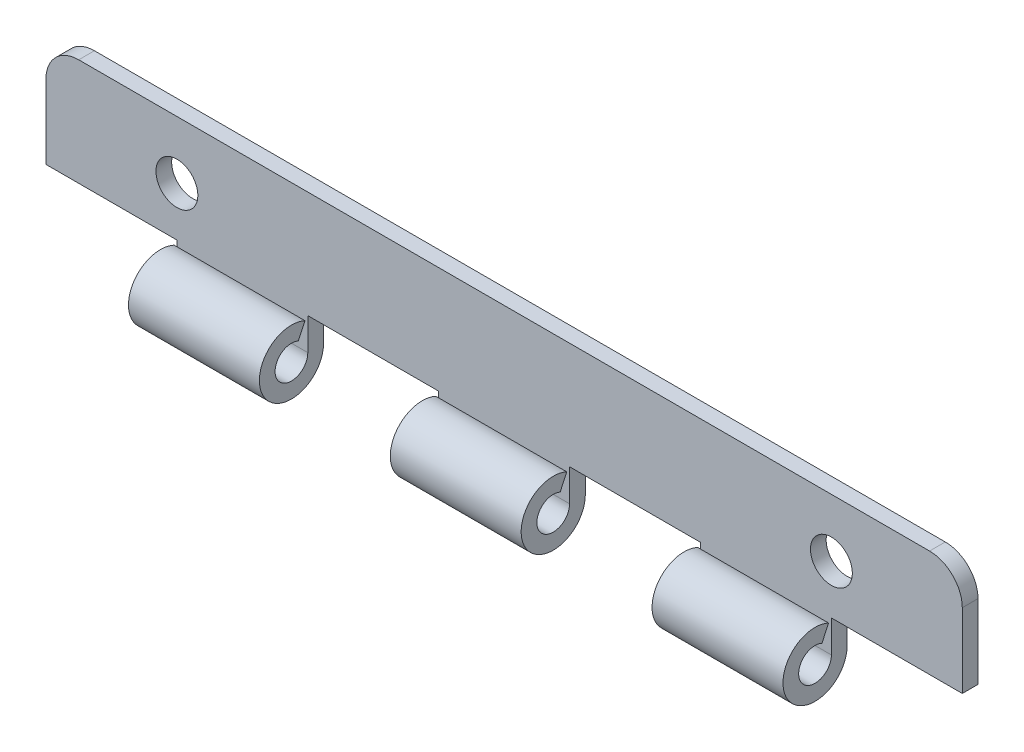
SolidWorks part; units mm, degrees
other "Bottom Leaf"
other "Top Leaf"
other "Pin" parameters "D1"=17.6771, "Angle"=25, "D2"=74.218, "Pin Diameter"=3.175, "D3"=51.2197, "Knuckle Diameter"=28.575, "Leaf Thickness"=1.524, "Overall Width"=26.9875, "Length"=609.6, "Break Line"=101.6, "Knuckle Length"=12.7, "Chamfer"=0.3175
ref_plane "Front Plane" through (0, 0, 0) normal (0, 0, 1) x (1, 0, 0)
ref_plane "Top Plane" through (0, 0, 0) normal (0, 1, 0) x (1, 0, 0)
ref_plane "Right Plane" through (0, 0, 0) normal (1, 0, 0) x (0, 0, -1)
sketch "Sketch1" plane through (0, 0, 0) normal (1, 0, 0) x (0, 0, -1)
  line L0 (3.1115, 0) -> (3.1115, -13.4937) construction
  line L1 (3.1115, -13.4937) -> (1.5875, -13.4937) construction
  line L2 (1.5875, -13.4937) -> (1.5875, -2.6761) construction
  line L3 (0, 1.5875) -> (0, 3.1115) construction
  line L4 (0.6709, 1.4388) -> (1.315, 2.82) construction
  line L5 (0, -1.5875) -> (0, -3.1115) construction
  line L6 (0.6709, -1.4388) -> (1.315, -2.82) construction
  line L7 (3.1115, 0) -> (3.1115, 13.4937) construction
  line L8 (3.1115, 13.4937) -> (1.5875, 13.4937) construction
  line L9 (1.5875, 13.4937) -> (1.5875, 2.6761) construction
  line L10 (0, 3.1115) -> (3.1115, 3.1115) construction
  line L11 (0, -3.1115) -> (3.1115, -3.1115) construction
  line L12 (1.5875, -2.6761) -> (1.5875, 2.6761) construction
  line L13 (1.5875, 3.1369) -> (3.1115, 3.1369) construction
  circle A0 centre (0, 0) radius 1.5875 construction
  circle A1 centre (0, 0) radius 3.1115 construction
  point P3 (0, 1.5875)
  point P4 (0, -1.5875)
  point P5 (-1.5875, 0)
  point P6 (1.5875, 0)
  point P8 (-3.1115, 0)
  point P9 (0, 3.1115)
  point P10 (3.1115, 0)
  point P11 (0, -3.1115)
  point P17 (1.5875, -13.4937)
  point P18 (3.1115, -13.4937)
  point P22 (1.5875, -2.6761)
  point P24 (0.6709, 1.4388)
  point P25 (1.315, 2.82)
  point P30 (0.6709, -1.4388)
  point P31 (1.315, -2.82)
  point P34 (1.5875, 2.6761)
  point P36 (1.5875, 13.4937)
  point P37 (3.1115, 13.4937)
  point P40 (3.1115, -3.1115)
  point P41 (3.1115, 3.1115)
  point P44 (1.5875, 3.1369)
  point P45 (3.1115, 3.1369)
  dimension "D1" = 25
  dimension "Knuckle Diameter" = 6.223
  dimension "D2" = 0.0254
sketch "Sketch2" plane through (0, 0, 0) normal (0, 0, 1) x (1, 0, 0)
  line L0 (304.8, 13.4937) -> (-304.8, 13.4937) construction
  line L2 (304.8, -13.4937) -> (-304.8, -13.4938) construction
  line L4 (-304.8, -13.4938) -> (-304.8, 13.4937) construction
  line L5 (304.8, -13.4937) -> (304.8, 13.4937) construction
  line L6 (304.8, 3.1115) -> (-304.8, 3.1115) construction
  line L7 (-304.8, -3.1115) -> (304.8, -3.1115) construction
  line L8 (304.8, 0) -> (-304.8, 0) construction
  line L9 (203.2, -13.4937) -> (203.2, 13.4937) construction
  line L10 (-203.2, -13.4938) -> (-203.2, 13.4937) construction
  line L11 (0, -13.4937) -> (0, 13.4937) construction
  line L12 (304.8, 2.794) -> (304.4825, 3.1115) construction
  point P4 (0, 13.4937)
  point P9 (0, -13.4937)
  point P10 (-304.8, -13.4938)
  point P12 (-304.8, 13.4937)
  point P13 (304.8, -13.4937)
  point P14 (304.8, 13.4937)
  point P18 (292.1, -3.1115)
  point P19 (-304.8, -3.1115)
  point P20 (-304.8, 3.1115)
  point P21 (304.8, -3.1115)
  point P22 (304.8, 3.1115)
  point P28 (0, 0)
  point P30 (-304.8, 0)
  point P31 (304.8, 0)
  point P34 (203.2, 0)
  point P35 (203.2, -13.4937)
  point P36 (203.2, 13.4937)
  point P39 (-203.2, 0)
  point P40 (-203.2, 13.4937)
  point P41 (-203.2, -13.4938)
  point P44 (0, 0)
  point P45 (279.4, -3.1115)
  point P49 (304.4825, 3.1115)
  point P50 (304.8, 2.794)
  dimension "D1" = 12.7
  dimension "D2" = 45
ref_plane "Plane1" through (304.8, 0, 0) normal (1, 0, 0) x (0, 0, -1)
sketch "Sketch3" plane through (0, 0, 0) normal (1, 0, 0) x (0, 0, -1)
  line L0 (1.5875, 0) -> (1.5875, -2.6761)
  line L2 (0.6709, -1.4388) -> (1.315, -2.82) construction
  line L3 (0.6709, -1.4388) -> (1.315, -2.82)
  line L4 (1.5875, -13.4937) -> (1.5875, -2.6761) construction
  line L5 (1.5875, -13.4937) -> (1.5875, -2.6761)
  line L6 (3.1115, 0) -> (3.1115, -13.4937) construction
  line L7 (3.1115, 0) -> (3.1115, -13.4937)
  line L8 (3.1115, -13.4937) -> (1.5875, -13.4937) construction
  line L9 (3.1115, -13.4937) -> (1.5875, -13.4937)
  circle A0 centre (0, 0) radius 3.1115 construction
  arc A1 (3.1115, 0) -> (1.315, -2.82) centre (0, 0) ccw
  circle A2 centre (0, 0) radius 1.5875 construction
  arc A3 (1.5875, 0) -> (0.6709, -1.4388) centre (0, 0) ccw
extrude "Boss-Extrude1" add sketch "Sketch3" along normal mid plane 609.6
sketch "Sketch4" plane through (0, 0, 0) normal (0, 0, 1) x (1, 0, 0)
  line L0 (292.1, -3.1115) -> (292.1, 3.1115)
  line L1 (304.8, 3.1115) -> (-304.8, 3.1115) construction
  line L2 (292.1, 3.1115) -> (304.8, 3.1115)
  line L3 (304.8, 3.1115) -> (304.8, -3.1115)
  line L4 (304.8, -3.1115) -> (292.1, -3.1115)
extrude "Cut-Extrude1" cut sketch "Sketch4" against normal through all both and the other way through all
pattern_linear "LPattern1" count 24 spacing 25.4 along (-1, 0, 0) of "Cut-Extrude1"
sketch "Sketch5" plane through (304.8, 0, 0) normal (1, 0, 0) x (0, 0, -1)
  line L0 (1.5875, 13.4937) -> (1.5875, 2.6761) construction
  line L1 (3.1115, 0) -> (3.1115, 13.4937) construction
  line L3 (1.5875, 13.4937) -> (1.5875, 2.6761)
  line L4 (3.1115, 0) -> (3.1115, 13.4937)
  line L6 (3.1115, 13.4937) -> (1.5875, 13.4937) construction
  line L7 (3.1115, 13.4937) -> (1.5875, 13.4937)
  line L8 (0.6709, 1.4388) -> (1.315, 2.82) construction
  line L9 (0.6709, 1.4388) -> (1.315, 2.82)
  line L10 (1.5875, 2.6761) -> (1.5875, 0)
  circle A0 centre (0, 0) radius 1.5875 construction
  circle A1 centre (0, 0) radius 3.1115 construction
  arc A2 (0.6709, 1.4388) -> (1.5875, 0) centre (0, 0) ccw
  arc A3 (1.315, 2.82) -> (3.1115, 0) centre (0, 0) ccw
extrude "Boss-Extrude2" add sketch "Sketch5" against normal blind 609.6 separate body
sketch "Sketch6" plane through (0, 0, 0) normal (0, 0, 1) x (1, 0, 0)
  line L0 (279.4, -3.1115) -> (279.4, 3.1115)
  line L1 (304.8, 3.1115) -> (-304.8, 3.1115) construction
  line L2 (279.4, 3.1115) -> (292.1, 3.1115)
  line L3 (292.1, 3.1115) -> (292.1, -3.1115)
  line L4 (292.1, -3.1115) -> (279.4, -3.1115)
extrude "Cut-Extrude2" cut sketch "Sketch6" against normal through all both and the other way through all
pattern_linear "LPattern2" count 24 spacing 25.4 along (-1, 0, 0) of "Cut-Extrude2"
sketch "Sketch7" plane through (304.8, 0, 0) normal (1, 0, 0) x (0, 0, -1)
  circle A0 centre (0, 0) radius 1.5875 construction
  circle A1 centre (0, 0) radius 1.5875
extrude "Boss-Extrude3" add sketch "Sketch7" against normal blind 609.6 separate body
chamfer "Chamfer1" distance 0.3175 angle 45 2 edges at (-304.8, 0, -1.5875) (304.8, 0, -1.5875)
sketch "Sketch8" plane through (-304.8, 0, 0) normal (-1, 0, 0) x (0, 0, 1)
  line L1 (-5.8812, 15.0331) -> (5.8812, 15.0331)
  line L2 (-5.8812, 15.0331) -> (-5.8812, -15.0331)
  line L3 (-5.8812, -15.0331) -> (5.8812, -15.0331)
  line L4 (5.8812, 15.0331) -> (5.8812, -15.0331)
  line L5 (-5.8812, 15.0331) -> (5.8812, -15.0331) construction
  line L6 (-5.8812, -15.0331) -> (5.8812, 15.0331) construction
  point P0 (0, 0)
extrude "Cut-Extrude3" cut sketch "Sketch8" against normal through all from offset 88.9 offset against normal yes
delete or keep bodies "Body-Delete/Keep 1" type delete bodies bodies 185
delete or keep bodies "Body-Delete/Keep 3" type delete bodies bodies 184
fillet "Fillet1" radius 3.175 2 edges at (-304.8, 13.4937, -2.3495) (-215.9, 13.4937, -2.3495)
sketch "Sketch9" plane through (0, 0, -3.1115) normal (0, 0, -1) x (-1, 0, 0)
  circle A0 centre (228.6, 7.874) radius 2.032
  circle A1 centre (292.1, 7.874) radius 2.032
  circle A2 centre (228.6, 7.874) radius 2.032 construction
  circle A3 centre (292.1, 7.874) radius 2.032 construction
  dimension "D1" = 4.064
extrude "Cut-Extrude4" cut sketch "Sketch9" against normal through all
equation "\"D1@Sketch1\"=\"Angle@Sketch1\""
equation "\"D1@Sketch2\"=\"Knuckle Length@Sketch2\""
equation "\"D1@Boss-Extrude1\" = \"Length@Sketch2\""
equation "\"D1@LPattern1\" = \"Length@Sketch2\" /  ( \"Knuckle Length@Sketch2\" * 2 ) "
equation "\"D3@LPattern1\" = \"Knuckle Length@Sketch2\" * 2"
equation "\"D1@Boss-Extrude2\"=\"Length@Sketch2\""
equation "\"Chamfer@Sketch2\" = \"Pin Diameter@Sketch1\" * .1"
equation "\"D1@Boss-Extrude3\" = \"Length@Sketch2\""
equation "\"D1@Chamfer1\"=\"Chamfer@Sketch2\""
equation "\"D3@LPattern2\" = \"Knuckle Length@Sketch2\" * 2"
equation "\"D1@LPattern2\" = \"Length@Sketch2\" /  ( \"Knuckle Length@Sketch2\" * 2 ) "
